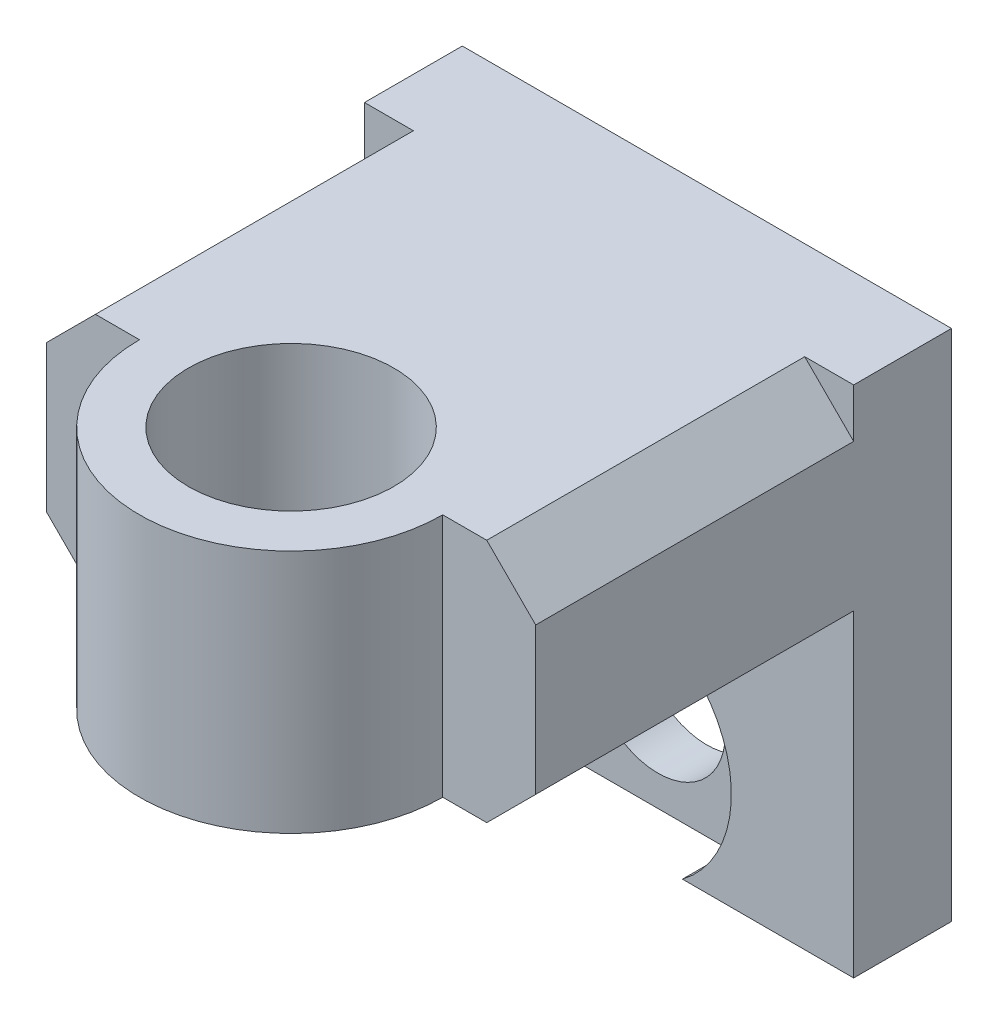
SolidWorks part; units mm, degrees
ref_plane "前视基准面" through (0, 0, 0) normal (0, 0, 1) x (1, 0, 0)
ref_plane "上视基准面" through (0, 0, 0) normal (0, 1, 0) x (1, 0, 0)
ref_plane "右视基准面" through (0, 0, 0) normal (1, 0, 0) x (0, 0, -1)
sketch "草图1" plane through (0, 0, 0) normal (0, 0, 1) x (1, 0, 0)
  line L0 (10, 0) -> (10, -32) construction
  line L1 (0, 0) -> (20, 0)
  line L2 (0, 0) -> (0, -32)
  line L3 (0, -32) -> (20, -32)
  line L4 (20, 0) -> (20, -32)
  circle A0 centre (10, -4) radius 2.75
  circle A1 centre (10, -28) radius 2.75
  point P11 (20, -16)
  dimension "D3" = 5.5
  dimension "D4" = 5.5
  dimension "D5" = 24
  dimension "D6" = 12
  dimension "D7" = 10
  dimension "D1" = 32
  dimension "D2" = 20
extrude "凸台-拉伸1" add sketch "草图1" along normal blind 4
sketch "草图2" plane through (0, 0, 4) normal (0, 0, 1) x (1, 0, 0)
  line L0 (0, 0) -> (0, -32) construction
  line L1 (0, -11) -> (20, -11)
  line L2 (0, -11) -> (0, -21)
  line L3 (0, -21) -> (20, -21)
  line L4 (20, -11) -> (20, -21)
  line L5 (20, -32) -> (20, 0) construction
  line L6 (20, 0) -> (0, 0) construction
  dimension "D1" = 10
  dimension "D2" = 11
extrude "凸台-拉伸2" add sketch "草图2" along normal blind 13
sketch "草图4" plane through (0, -21, 0) normal (0, -1, 0) x (1, 0, 0)
  line L0 (0, 17) -> (20, 17) construction
  circle A0 centre (10, 17) radius 6.2
  dimension "D1" = 12.4
extrude "凸台-拉伸3" add sketch "草图4" against normal up to surface (10 mm away) up to face at (10, -11, 10.5)
sketch "草图5" plane through (0, -11, 0) normal (0, 1, 0) x (1, 0, 0)
  circle A0 centre (10, -17) radius 4.2
  dimension "D1" = 8.4
extrude "切除-拉伸1" cut sketch "草图5" against normal blind 13
chamfer "倒角1" distance 2 angle 45 4 edges at (20, -11, 10.5) (20, -21, 10.5) (0, -21, 10.5) (0, -11, 10.5)
sketch "草图6" plane through (0, 0, 4) normal (0, 0, 1) x (1, 0, 0)
  circle A0 centre (10, -28) radius 5
  circle A1 centre (10, -4) radius 5
  dimension "D1" = 10
  dimension "D2" = 10
extrude "切除-拉伸2" cut sketch "草图6" against normal blind 2
sketch "草图7" plane through (0, 0, 4) normal (0, 0, 1) x (1, 0, 0)
  line L0 (0, 0) -> (0, -13) construction
  line L1 (0, -11) -> (20, -11)
  line L2 (0, -11) -> (0, 0)
  line L3 (0, 0) -> (20, 0)
  line L4 (20, -11) -> (20, 0)
extrude "切除-拉伸3" cut sketch "草图7" against normal through all
